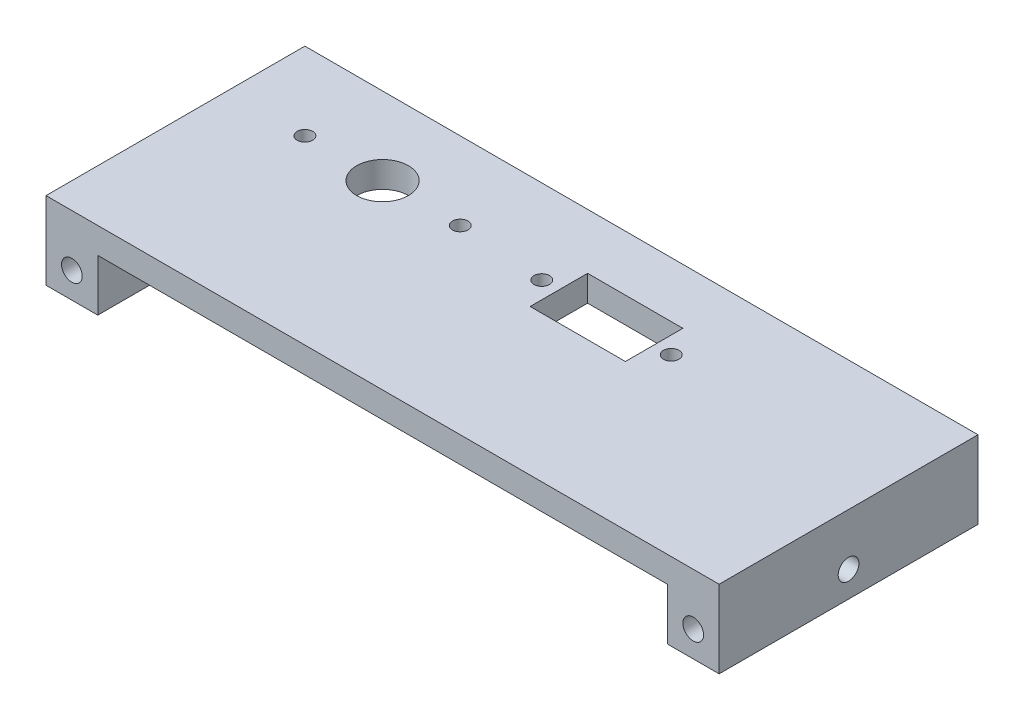
SolidWorks part; units mm, degrees
other "Marcação1"
sketch "Esboço3" plane through (-130, 13, -50) normal (0, 1, 0) x (1, 0, 0)
sketch "Esboço4" plane through (-130, 15, -50) normal (0, 1, 0) x (1, 0, 0)
sketch "Esboço9" plane through (-130, 15, -50) normal (0, 1, 0) x (1, 0, 0)
sketch "Esboço11" plane through (-130, 15, -50) normal (0, 1, 0) x (1, 0, 0)
ref_plane "Plano frontal" through (0, 0, 0) normal (0, 0, 1) x (1, 0, 0)
ref_plane "Plano superior" through (0, 0, 0) normal (0, 1, 0) x (1, 0, 0)
ref_plane "Plano direito" through (0, 0, 0) normal (1, 0, 0) x (0, 0, -1)
sketch "Esboço1" plane through (0, 0, 0) normal (0, 1, 0) x (1, 0, 0)
  line L1 (-130, 50) -> (0, 50)
  line L2 (-130, 50) -> (-130, 0)
  line L3 (-130, 0) -> (0, 0)
  line L4 (0, 50) -> (0, 0)
extrude "Ressalto-extrusão1" add sketch "Esboço1" along normal blind 15
sketch "Esboço2" plane through (0, 0, -50) normal (0, 0, -1) x (-1, 0, 0)
  line L1 (10, 0) -> (10, 15) construction
  line L2 (0, 0) -> (130, 0) construction
  line L3 (0, 15) -> (130, 15) construction
  line L4 (120, 0) -> (120, 15) construction
  line L5 (0, 15) -> (0, 0) construction
  line L6 (130, 15) -> (130, 0) construction
  line L7 (0, 10) -> (130, 10) construction
  line L9 (10, 0) -> (120, 0)
  line L10 (10, 0) -> (10, 10)
  line L11 (10, 10) -> (120, 10)
  line L12 (120, 0) -> (120, 10)
  dimension "D1" = 10
  dimension "D2" = 10
  dimension "D3" = 10
extrude "Corte-extrusão1" cut sketch "Esboço2" against normal blind 51
sketch "Esboço5" plane through (0, 0, -50) normal (0, 0, -1) x (-1, 0, 0)
  circle A2 centre (125, 5) radius 2
  circle A3 centre (5, 5) radius 2
extrude "Corte-extrusão2" cut sketch "Esboço5" against normal blind 10
sketch "Esboço6" plane through (0, 0, 0) normal (0, 0, 1) x (1, 0, 0)
  circle A0 centre (-125, 5) radius 2
  circle A1 centre (-5, 5) radius 2
extrude "Corte-extrusão3" cut sketch "Esboço6" against normal blind 10
sketch "Esboço7" plane through (0, 0, 0) normal (1, 0, 0) x (0, 0, -1)
  circle A0 centre (25, 5) radius 2
extrude "Corte-extrusão4" cut sketch "Esboço7" against normal blind 10
sketch "Esboço8" plane through (-130, 0, 0) normal (-1, 0, 0) x (0, 0, 1)
  circle A0 centre (-25, 5) radius 2
extrude "Corte-extrusão5" cut sketch "Esboço8" against normal blind 10
sketch "Esboço13" plane through (0, 15, 0) normal (0, 1, 0) x (1, 0, 0)
  line L0 (-100, 50) -> (-100, 0) construction
  line L1 (0, 50) -> (-130, 50) construction
  line L2 (-130, 0) -> (0, 0) construction
  line L3 (-130, 35) -> (0, 35) construction
  line L4 (-130, 50) -> (-130, 0) construction
  line L5 (0, 0) -> (0, 50) construction
  line L6 (-115, 50) -> (-115, 0) construction
  line L7 (-85, 50) -> (-85, 0) construction
  circle A0 centre (-115, 35) radius 1.5
  circle A1 centre (-100, 35) radius 5
  circle A2 centre (-85, 35) radius 1.5
  dimension "D5" = 3
  dimension "D6" = 3
  dimension "D7" = 10
  dimension "D1" = 30
  dimension "D2" = 15
  dimension "D3" = 15
  dimension "D4" = 15
extrude "Corte-extrusão8" cut sketch "Esboço13" against normal blind 10
sketch "Esboço14" plane through (0, 15, 0) normal (0, 1, 0) x (1, 0, 0)
  line L0 (-43, 0) -> (-43, 50) construction
  line L1 (-130, 0) -> (0, 0) construction
  line L2 (0, 50) -> (-130, 50) construction
  line L3 (0, 33.75) -> (-130, 33.75) construction
  line L4 (0, 0) -> (0, 50) construction
  line L5 (-130, 50) -> (-130, 0) construction
  line L6 (0, 28.2) -> (-130, 28.2) construction
  line L7 (0, 39.3) -> (-130, 39.3) construction
  line L8 (-68, 0) -> (-68, 50) construction
  line L9 (-46.3, 0) -> (-46.3, 50) construction
  line L10 (-64.7, 0) -> (-64.7, 50) construction
  line L12 (-46.3, 28.2) -> (-64.7, 28.2)
  line L13 (-46.3, 28.2) -> (-46.3, 39.3)
  line L14 (-46.3, 39.3) -> (-64.7, 39.3)
  line L15 (-64.7, 28.2) -> (-64.7, 39.3)
  circle A0 centre (-68, 33.75) radius 1.5
  circle A1 centre (-43, 33.75) radius 1.5
  dimension "D8" = 3
  dimension "D9" = 3
  dimension "D1" = 16.25
  dimension "D2" = 43
  dimension "D3" = 25
  dimension "D4" = 5.55
  dimension "D5" = 5.55
  dimension "D6" = 3.3
  dimension "D7" = 3.3
extrude "Corte-extrusão9" cut sketch "Esboço14" against normal blind 10
